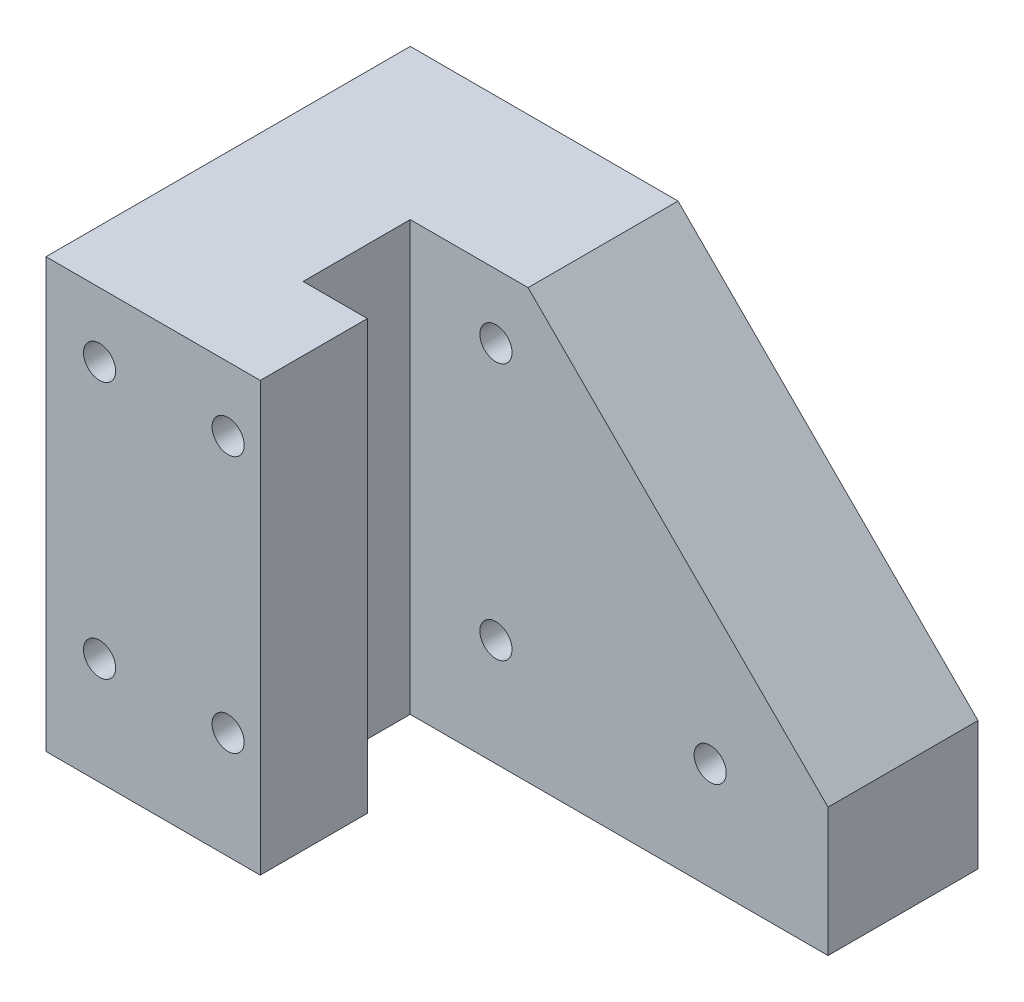
SolidWorks part; units mm, degrees
ref_plane "前视基准面" through (0, 0, 0) normal (0, 0, 1) x (1, 0, 0)
ref_plane "上视基准面" through (0, 0, 0) normal (0, 1, 0) x (1, 0, 0)
ref_plane "右视基准面" through (0, 0, 0) normal (1, 0, 0) x (0, 0, -1)
other "Configuration Table"
sketch "草图1" plane through (0, 0, 0) normal (0, 0, 1) x (1, 0, 0)
  line L1 (0, 0) -> (20, 0)
  line L2 (0, 0) -> (0, 40)
  line L3 (0, 40) -> (20, 40)
  line L4 (20, 0) -> (20, 40)
  dimension "D1" = 20
  dimension "D2" = 40
extrude "凸台-拉伸1" add sketch "草图1" along normal blind 34
sketch "草图2" plane through (0, 0, 34) normal (0, 0, 1) x (1, 0, 0)
  line L0 (0, 40) -> (0, 0) construction
  line L1 (0, 0) -> (20, 0) construction
  circle A0 centre (5, 34) radius 1.5
  circle A1 centre (5, 10) radius 1.5
  point P12 (0, 0)
  point P13 (0, 0)
  point P14 (0, 0)
  dimension "D1" = 3
  dimension "D2" = 3
  dimension "D3" = 5
  dimension "D4" = 24
  dimension "D5" = 10
extrude "切除-拉伸1" cut sketch "草图2" against normal through all
sketch "草图3" plane through (0, 0, 34) normal (0, 0, 1) x (1, 0, 0)
  line L0 (0, 0) -> (20, 0) construction
  line L1 (20, 0) -> (53, 0)
  line L2 (20, 0) -> (20, 40)
  line L3 (20, 40) -> (53, 40)
  line L4 (53, 0) -> (53, 40)
  line L5 (20, 40) -> (0, 40) construction
  line L6 (20, 0) -> (20, 40) construction
  dimension "D1" = 33
extrude "凸台-拉伸2" add sketch "草图3" along normal blind 14 from surface at -34 starting at face at (6.5, 34, 0)
sketch "草图4" plane through (0, 0, 0) normal (0, 0, -1) x (-1, 0, 0)
  line L0 (-25, 40) -> (-53, 40)
  line L1 (-53, 40) -> (0, 40) construction
  line L2 (-53, 40) -> (-53, 12)
  line L3 (-53, 40) -> (-53, 0) construction
  line L4 (-53, 12) -> (-25, 40)
  dimension "D1" = 28
  dimension "D2" = 28
extrude "切除-拉伸2" cut sketch "草图4" against normal through all
sketch "草图5" plane through (0, 0, 0) normal (0, 0, -1) x (-1, 0, 0)
  line L0 (-22, 34) -> (-5, 34) construction
  line L1 (-22, 10) -> (-5, 10) construction
  circle A0 centre (-22, 34) radius 1.5
  circle A1 centre (-22, 10) radius 1.5
  circle A2 centre (-5, 34) radius 1.5 construction
  circle A3 centre (-42, 10) radius 1.5
  dimension "D1" = 3
  dimension "D2" = 3
  dimension "D4" = 3
  dimension "D3" = 17
  dimension "D5" = 20
extrude "切除-拉伸3" cut sketch "草图5" against normal through all
sketch "草图6" plane through (0, 0, 0) normal (0, -1, 0) x (1, 0, 0)
  line L1 (20, 14) -> (14, 14)
  line L2 (20, 14) -> (20, 24)
  line L3 (20, 24) -> (14, 24)
  line L4 (14, 14) -> (14, 24)
  dimension "D1" = 6
  dimension "D2" = 10
extrude "切除-拉伸4" cut sketch "草图6" against normal through all
sketch "草图7" plane through (0, 0, 34) normal (0, 0, 1) x (1, 0, 0)
  line L0 (17, 10) -> (5, 10) construction
  line L1 (17, 34) -> (5, 34) construction
  circle A0 centre (17, 34) radius 1.5
  circle A1 centre (17, 10) radius 1.5
  circle A2 centre (5, 34) radius 1.5 construction
  circle A3 centre (5, 10) radius 1.5 construction
  point P4 (0, 0)
  point P9 (0, 0)
  dimension "D1" = 3
  dimension "D2" = 3
  dimension "D3" = 12
extrude "切除-拉伸5" cut sketch "草图7" against normal up to surface (10 mm away) up to face at (17, 20, 24)
